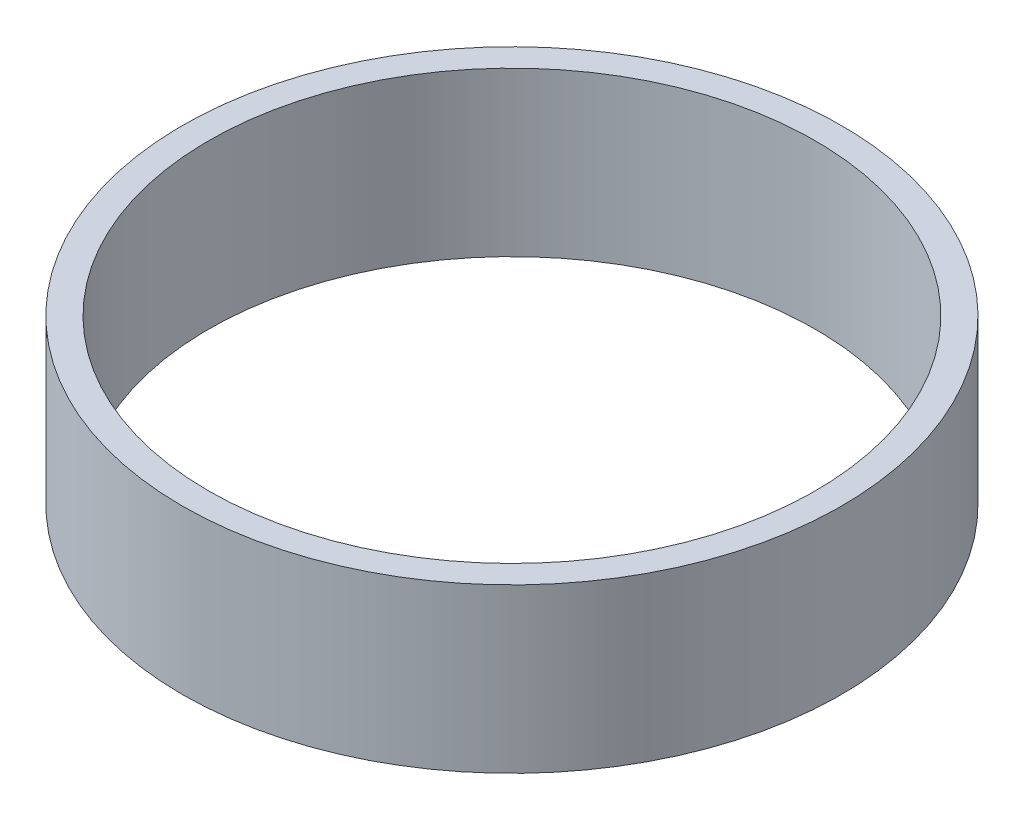
SolidWorks part; units mm, degrees
ref_plane "Plan de face" through (0, 0, 0) normal (0, 0, 1) x (1, 0, 0)
ref_plane "Plan de dessus" through (0, 0, 0) normal (0, 1, 0) x (1, 0, 0)
ref_plane "Plan de droite" through (0, 0, 0) normal (1, 0, 0) x (0, 0, -1)
sketch "Esquisse1" plane through (0, 0, 0) normal (0, 1, 0) x (1, 0, 0)
  circle A0 centre (0, 0) radius 12.115
  dimension "D1" = 24.23
extrude "Boss.-Extru.1" add sketch "Esquisse1" along normal blind 6
sketch "Esquisse2" plane through (0, 6, 0) normal (0, 1, 0) x (1, 0, 0)
  circle A0 centre (0, 0) radius 11.15
  dimension "D1" = 22.3
extrude "Enlèv. mat.-Extru.1" cut sketch "Esquisse2" against normal blind 10
